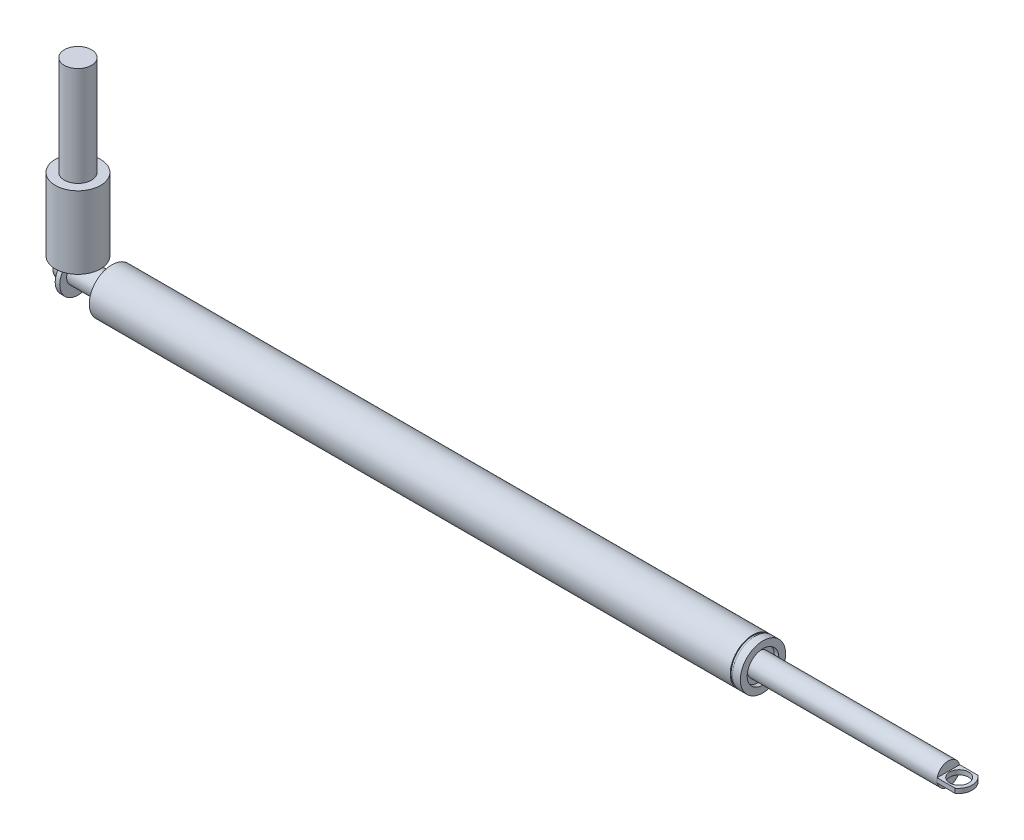
SolidWorks part; units mm, degrees
ref_plane "前视基准面" through (0, 0, 0) normal (0, 0, 1) x (1, 0, 0)
ref_plane "上视基准面" through (0, 0, 0) normal (0, 1, 0) x (1, 0, 0)
ref_plane "右视基准面" through (0, 0, 0) normal (1, 0, 0) x (0, 0, -1)
other "Configuration Table"
ref_plane "基准面1" through (0, 0, 0) normal (1, 0, 0) x (0, 0, -1)
sketch "草图2" plane through (0, 0, 0) normal (1, 0, 0) x (0, 0, -1)
  circle A0 centre (0, 12.0525) radius 2.5
extrude "凸台-拉伸2" add sketch "草图2" along normal blind 7.5
ref_plane "基准面4" through (0, 12, 0) normal (0, 1, 0) x (1, 0, 0)
ref_plane "基准面5" through (0, 45.9475, 0) normal (0, 1, 0) x (1, 0, 0)
sketch "草图10" plane through (0, 45.9475, 0) normal (0, 1, 0) x (1, 0, 0)
  circle A0 centre (0, 0) radius 3
extrude "凸台-拉伸3" add sketch "草图10" against normal blind 15 separate body
ref_plane "基准面6" through (0, 30.9475, 0) normal (0, 1, 0) x (1, 0, 0)
sketch "草图11" plane through (0, 30.9475, 0) normal (0, 1, 0) x (1, 0, 0)
  circle A0 centre (0, 0) radius 5
extrude "凸台-拉伸4" add sketch "草图11" against normal blind 16
sketch "草图12" plane through (0, 14.9475, 0) normal (0, -1, 0) x (1, 0, 0)
  line L0 (0, 2.5289) -> (-1, 2.5289)
  line L1 (0, -2.75) -> (0, 2.75) construction
  line L2 (-1, 2.5289) -> (-1, -2.4711)
  line L3 (-1, -2.4711) -> (0, -2.4711)
  line L4 (0, 2.5289) -> (0, -2.4711)
extrude "凸台-拉伸6" add sketch "草图12" along normal blind 0.4
sketch "草图13" plane through (0, 0, 0) normal (1, 0, 0) x (0, 0, -1)
  line L0 (-2.5289, 14.5475) -> (2.4711, 14.5475)
  arc A0 (-2.5289, 14.5475) -> (2.4711, 14.5475) centre (-0.0289, 11.425) ccw
extrude "凸台-拉伸7" add sketch "草图13" against normal blind 1
sketch "草图14" plane through (-1, 0, 0) normal (-1, 0, 0) x (0, 0, 1)
  circle A0 centre (0.0289, 12.0475) radius 2.5
extrude "凸台-拉伸10" add sketch "草图14" along normal blind 2
ref_plane "基准面8" through (0, 0, 0) normal (1, 0, 0) x (0, 0, -1)
sketch "草图19" plane through (0, 12, 0) normal (0, 1, 0) x (1, 0, 0)
  circle A3 centre (194.8822, 0) radius 2.1032
sketch "草图21" plane through (0, 45.9475, 0) normal (0, 1, 0) x (1, 0, 0)
  circle A0 centre (0, 0) radius 3
extrude "凸台-拉伸14" add sketch "草图21" along normal blind 2
ref_plane "基准面10" through (7.5, 0, 0) normal (1, 0, 0) x (0, 0, -1)
sketch "草图25" plane through (7.5, 0, 0) normal (1, 0, 0) x (0, 0, -1)
  line L0 (2.1032, 12) -> (-2.1032, 12) construction
  circle A0 centre (0, 12) radius 5
extrude "凸台-拉伸16" add sketch "草图25" along normal blind 144
sketch "草图26" plane through (151.5, 0, 0) normal (1, 0, 0) x (0, 0, -1)
  line L0 (2.1032, 12) -> (-2.1032, 12) construction
  circle A0 centre (0, 12) radius 3.5
extrude "切除-拉伸3" cut sketch "草图26" against normal blind 1
sketch "草图27" plane through (150.5, 0, 0) normal (1, 0, 0) x (0, 0, -1)
  line L0 (2.1032, 12) -> (-2.1032, 12) construction
  circle A0 centre (0, 12) radius 2.5
extrude "凸台-拉伸17" add sketch "草图27" along normal blind 42
sketch "草图30" plane through (0, 12, 0) normal (0, 1, 0) x (1, 0, 0)
  line L0 (192.5, 2.5) -> (196.5, 2.5)
  line L1 (192.5, -2.5) -> (196.5, -2.5)
  line L2 (192.5, 2.5) -> (192.5, -2.5)
  arc A0 (196.5, 2.5) -> (196.5, -2.5) centre (194.6675, 0) cw
  dimension "D1" = 4
extrude "凸台-拉伸18" add sketch "草图30" along normal mid plane 1
extrude "切除-拉伸4" cut sketch "草图19" against normal mid plane 1 contours A3
sketch "草图31" plane through (0, 47.9475, 0) normal (0, 1, 0) x (1, 0, 0)
  circle A0 centre (0, 0) radius 3
extrude "凸台-拉伸19" add sketch "草图31" along normal blind 3
sketch "草图32" plane through (0, 50.9475, 0) normal (0, 1, 0) x (1, 0, 0)
  circle A0 centre (0, 0) radius 3
extrude "凸台-拉伸20" add sketch "草图32" along normal blind 2
ref_plane "基准面11" through (149.5, 0, 0) normal (1, 0, 0) x (0, 0, -1)
sketch "草图33" plane through (149.5, 0, 0) normal (1, 0, 0) x (0, 0, -1)
  circle A0 centre (0, 12) radius 4.8
extrude "切除-拉伸6" cut sketch "草图33" against normal mid plane 0.5 flip side to cut
